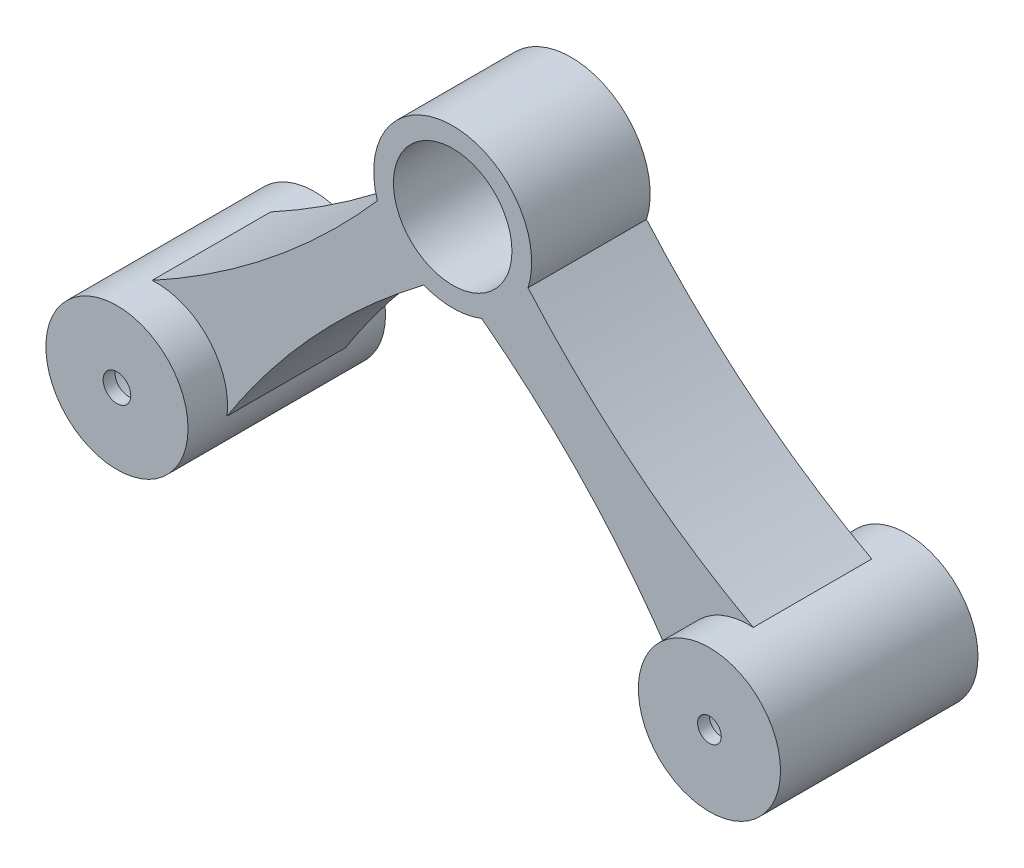
SolidWorks part; units mm, degrees
ref_plane "Front Plane" through (0, 0, 0) normal (0, 0, 1) x (1, 0, 0)
ref_plane "Top Plane" through (0, 0, 0) normal (0, 1, 0) x (1, 0, 0)
ref_plane "Right Plane" through (0, 0, 0) normal (1, 0, 0) x (0, 0, -1)
sketch "Sketch1" plane through (0, 0, 0) normal (0, 0, 1) x (1, 0, 0)
  circle A0 centre (0, 0) radius 18
  circle A1 centre (0, 0) radius 12.8
extrude "Boss-Extrude1" add sketch "Sketch1" against normal blind 50
sketch "Sketch2" plane through (0, 0, 0) normal (0, 0, 1) x (1, 0, 0)
  circle A0 centre (0, 0) radius 12.8
  circle A1 centre (0, 0) radius 3.5
extrude "Boss-Extrude2" add sketch "Sketch2" against normal blind 3
sketch "Sketch3" plane through (0, 0, 0) normal (0, 0, 1) x (1, 0, 0)
  line L0 (0, 0) -> (150, 0) construction
  line L1 (0, 0) -> (75, 69.9386) construction
  line L2 (75, 0) -> (75, 69.9386) construction
  line L3 (150, 0) -> (75, 69.9386) construction
  dimension "D1" = 43
ref_plane "Plane1" through (0, 0, -10) normal (0, 0, 1) x (1, 0, 0)
sketch "Sketch4" plane through (0, 0, -10) normal (0, 0, 1) x (1, 0, 0)
  circle A0 centre (75, 69.9386) radius 20
  circle A1 centre (75, 69.9386) radius 15
extrude "Boss-Extrude3" add sketch "Sketch4" against normal blind 30 separate body
sketch "Sketch6" plane through (0, 0, -40) normal (0, 0, -1) x (-1, 0, 0)
  line L0 (-75, 69.9386) -> (0, 0) construction
  arc A0 (-67.6611, 51.3338) -> (-55.9285, 63.9154) centre (-75, 69.9386) ccw
  arc A1 (1.0948, 17.9667) -> (-17.8465, -2.3455) centre (0, 0) ccw
  spline S0 degree 2 poles (-67.6611, 51.3338) (-37.5001, 28.4545) (-17.8465, -2.3455) knots 0 0 0 0.881213 0.881213 0.881213
  spline S1 degree 2 poles (-55.9285, 63.9154) (-31.0011, 35.4239) (1.0948, 17.9667) knots 0 0 0 0.881213 0.881213 0.881213
extrude "Boss-Extrude4" add sketch "Sketch6" against normal blind 30
sketch "Sketch7" plane through (0, 0, -40) normal (0, 0, -1) x (-1, 0, 0)
  line L0 (-75, 69.9386) -> (0, 0) construction
  arc A1 (-64.4405, 52.9534) -> (-57.3196, 60.5897) centre (-75, 69.9386) ccw
  arc A2 (-6.3362, 16.8479) -> (-17.2489, 5.1455) centre (0, 0) ccw
  spline S0 degree 2 poles (-64.4405, 52.9534) (-37.8822, 31.6253) (-17.2489, 5.1455) knots 0 0 0 0.925027 0.925027 0.925027
  spline S1 degree 2 poles (-57.3196, 60.5897) (-34.1908, 35.5838) (-6.3362, 16.8479) knots 0 0 0 0.925027 0.925027 0.925027
extrude "Cut-Extrude1" cut sketch "Sketch7" against normal blind 20
sketch "Sketch8" plane through (0, 0, -40) normal (0, 0, -1) x (-1, 0, 0)
  line L0 (-51.3126, 41.7696) -> (-45.1499, 48.1803)
  line L1 (-27.0421, 17.0404) -> (-18.8852, 25.7875)
  parabola Q0 (-64.4405, 52.9534) -> (-17.2489, 5.1455) focus (-135.0417, -76.8626) apex (-27.0421, 17.0404) construction
  parabola Q1 (-51.3126, 41.7696) -> (-27.0421, 17.0404) focus (-135.0417, -76.8626) apex (-27.0421, 17.0404)
  parabola Q2 (-6.3362, 16.8479) -> (-57.3196, 60.5897) focus (67.2554, 140.0744) apex (-18.8852, 25.7875) construction
  parabola Q3 (-18.8852, 25.7875) -> (-45.1499, 48.1803) focus (67.2554, 140.0744) apex (-18.8852, 25.7875)
extrude "Boss-Extrude5" add sketch "Sketch8" against normal blind 5
ref_plane "Plane3" through (75, 0, 0) normal (1, 0, 0) x (0, 0, -1)
sketch "Sketch9" plane through (0, 0, 0) normal (0, 0, 1) x (1, 0, 0)
  circle A0 centre (150, 0) radius 18
  circle A1 centre (150, 0) radius 13
extrude "Boss-Extrude6" add sketch "Sketch9" against normal blind 50 separate body
sketch "Sketch10" plane through (0, 0, 0) normal (0, 0, 1) x (1, 0, 0)
  circle A0 centre (150, 0) radius 13
  circle A1 centre (150, 0) radius 3
extrude "Boss-Extrude7" add sketch "Sketch10" against normal blind 3
mirror "Mirror3" about plane through (75, 0, 0) normal (1, 0, 0) of "Boss-Extrude4"
mirror "Mirror4" about plane through (75, 0, 0) normal (1, 0, 0) of "Cut-Extrude1"
mirror "Mirror5" about plane through (75, 0, 0) normal (1, 0, 0) of "Boss-Extrude5"
